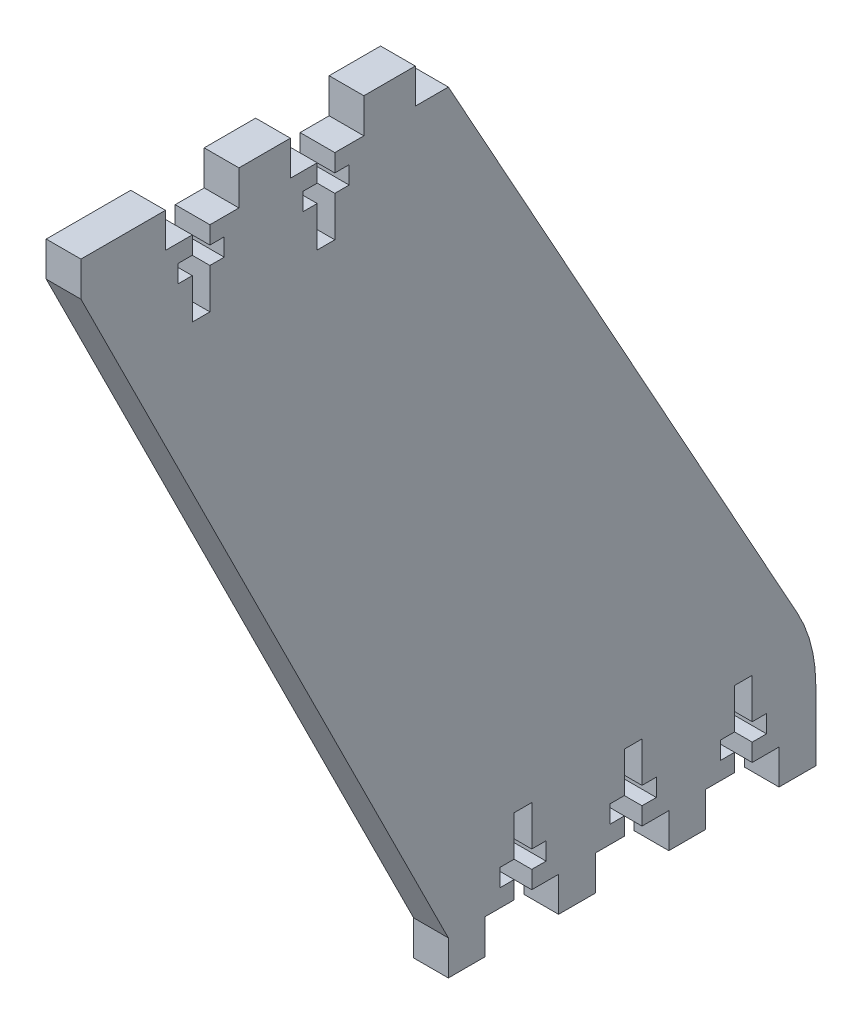
SolidWorks part; units mm, degrees
ref_plane "Front Plane" through (0, 0, 0) normal (0, 0, 1) x (1, 0, 0)
ref_plane "Top Plane" through (0, 0, 0) normal (0, 1, 0) x (1, 0, 0)
ref_plane "Right Plane" through (0, 0, 0) normal (1, 0, 0) x (0, 0, -1)
sketch "Sketch1" plane through (0, 0, 0) normal (1, 0, 0) x (0, 0, -1)
  line L0 (-74.3254, 0) -> (74.3254, 0) construction
  line L1 (-31.75, 0) -> (-95.25, 127.35)
  line L4 (-31.75, 0) -> (0, 17.1799) construction
  line L5 (-95.25, 127.35) -> (-95.25, 133.35)
  line L6 (-95.25, 133.35) -> (-80.645, 133.35)
  line L7 (-80.645, 133.35) -> (-80.645, 127.35)
  line L8 (-80.645, 127.35) -> (-67.945, 127.35)
  line L9 (-67.945, 127.35) -> (-67.945, 133.35)
  line L10 (-67.945, 133.35) -> (-59.055, 133.35)
  line L11 (-59.055, 133.35) -> (-59.055, 127.35)
  line L12 (-59.055, 127.35) -> (-46.355, 127.35)
  line L13 (-46.355, 127.35) -> (-46.355, 133.35)
  line L14 (-46.355, 133.35) -> (-37.465, 133.35)
  line L15 (-37.465, 133.35) -> (-37.465, 127.35)
  line L16 (-37.465, 127.35) -> (-31.75, 127.35)
  line L17 (-31.75, 0) -> (-31.75, -6)
  line L18 (-31.75, -6) -> (-25.4, -6)
  line L19 (-25.4, -6) -> (-25.4, 0)
  line L20 (-25.4, 0) -> (-12.7, 0)
  line L21 (-12.7, 0) -> (-12.7, -6)
  line L22 (-12.7, -6) -> (-6.35, -6)
  line L23 (-6.35, -6) -> (-6.35, 0)
  line L24 (-6.35, 0) -> (6.35, 0)
  line L25 (6.35, 0) -> (6.35, -6)
  line L26 (6.35, -6) -> (12.7, -6)
  line L27 (12.7, -6) -> (12.7, 0)
  line L28 (12.7, 0) -> (25.4, 0)
  line L29 (25.4, 0) -> (25.4, -6)
  line L30 (25.4, -6) -> (31.75, -6)
  line L31 (31.75, -6) -> (31.75, 0)
  line L32 (0, 17.1799) -> (31.75, 0) construction
  line L33 (0, 0) -> (0, 17.1799) construction
  line L34 (-63.5, 133.35) -> (-63.5, 108.2099) construction
  line L35 (31.75, 0) -> (31.75, 6.1358)
  line L36 (28.5696, 18.4423) -> (-31.75, 127.35)
  arc A0 (31.75, 6.1358) -> (28.5696, 18.4423) centre (6.35, 6.1358) ccw
  point P37 (-74.295, 127.35)
  point P38 (-52.705, 127.35)
  point P39 (-19.05, 0)
  point P40 (19.05, 0)
  point P44 (31.75, 12.7)
  line B0 (-18.8595, 13.05) -> (-18.8595, -5.9362) construction
  line B1 (-20.3835, 0) -> (-20.3835, 3.048)
  line B2 (-20.3835, 3.048) -> (-22.86, 3.048)
  line B3 (-22.86, 3.048) -> (-22.86, 6.096)
  line B4 (-22.86, 6.096) -> (-20.3835, 6.096)
  line B5 (-20.3835, 6.096) -> (-20.3835, 13.05)
  line B6 (-20.3835, 13.05) -> (-17.3355, 13.05)
  line B7 (-17.3355, 6.096) -> (-17.3355, 13.05)
  line B8 (-14.859, 6.096) -> (-17.3355, 6.096)
  line B9 (-14.859, 3.048) -> (-14.859, 6.096)
  line B10 (-17.3355, 3.048) -> (-14.859, 3.048)
  line B11 (-17.3355, 0) -> (-17.3355, 3.048)
  line B12 (0.1905, 13.05) -> (0.1905, -5.9362) construction
  line B13 (-1.3335, 0) -> (-1.3335, 3.048)
  line B14 (-1.3335, 3.048) -> (-3.81, 3.048)
  line B15 (-3.81, 3.048) -> (-3.81, 6.096)
  line B16 (-3.81, 6.096) -> (-1.3335, 6.096)
  line B17 (-1.3335, 6.096) -> (-1.3335, 13.05)
  line B18 (-1.3335, 13.05) -> (1.7145, 13.05)
  line B19 (1.7145, 6.096) -> (1.7145, 13.05)
  line B20 (4.191, 6.096) -> (1.7145, 6.096)
  line B21 (4.191, 3.048) -> (4.191, 6.096)
  line B22 (1.7145, 3.048) -> (4.191, 3.048)
  line B23 (1.7145, 0) -> (1.7145, 3.048)
  line B24 (19.2405, 13.05) -> (19.2405, -5.9362) construction
  line B25 (17.7165, 0) -> (17.7165, 3.048)
  line B26 (17.7165, 3.048) -> (15.24, 3.048)
  line B27 (15.24, 3.048) -> (15.24, 6.096)
  line B28 (15.24, 6.096) -> (17.7165, 6.096)
  line B29 (17.7165, 6.096) -> (17.7165, 13.05)
  line B30 (17.7165, 13.05) -> (20.7645, 13.05)
  line B31 (20.7645, 6.096) -> (20.7645, 13.05)
  line B32 (23.241, 6.096) -> (20.7645, 6.096)
  line B33 (23.241, 3.048) -> (23.241, 6.096)
  line B34 (20.7645, 3.048) -> (23.241, 3.048)
  line B35 (20.7645, 0) -> (20.7645, 3.048)
  line B36 (-74.4855, 114.3) -> (-74.4855, 133.2862) construction
  line B37 (-72.9615, 127.35) -> (-72.9615, 124.302)
  line B38 (-72.9615, 124.302) -> (-70.485, 124.302)
  line B39 (-70.485, 124.302) -> (-70.485, 121.254)
  line B40 (-70.485, 121.254) -> (-72.9615, 121.254)
  line B41 (-72.9615, 121.254) -> (-72.9615, 114.3)
  line B42 (-72.9615, 114.3) -> (-76.0095, 114.3)
  line B43 (-76.0095, 121.254) -> (-76.0095, 114.3)
  line B44 (-78.486, 121.254) -> (-76.0095, 121.254)
  line B45 (-78.486, 124.302) -> (-78.486, 121.254)
  line B46 (-76.0095, 124.302) -> (-78.486, 124.302)
  line B47 (-76.0095, 127.35) -> (-76.0095, 124.302)
  line B48 (-52.8955, 114.3) -> (-52.8955, 133.2862) construction
  line B49 (-51.3715, 127.35) -> (-51.3715, 124.302)
  line B50 (-51.3715, 124.302) -> (-48.895, 124.302)
  line B51 (-48.895, 124.302) -> (-48.895, 121.254)
  line B52 (-48.895, 121.254) -> (-51.3715, 121.254)
  line B53 (-51.3715, 121.254) -> (-51.3715, 114.3)
  line B54 (-51.3715, 114.3) -> (-54.4195, 114.3)
  line B55 (-54.4195, 121.254) -> (-54.4195, 114.3)
  line B56 (-56.896, 121.254) -> (-54.4195, 121.254)
  line B57 (-56.896, 124.302) -> (-56.896, 121.254)
  line B58 (-54.4195, 124.302) -> (-56.896, 124.302)
  line B59 (-54.4195, 127.35) -> (-54.4195, 124.302)
sketch_block_instance "Block-6-32x0_625 T-Nut block-1"
sketch_block "Block-6-32x0_625 T-Nut block" parameters "D1"=3.048, "D2"=13.05, "D3"=8.001, "D4"=3.048, "D5"=3.048
sketch_block_instance "Block-6-32x0_625 T-Nut block-2"
sketch_block_instance "Block-6-32x0_625 T-Nut block-3"
sketch_block_instance "Block-6-32x0_625 T-Nut block-5"
sketch_block_instance "Block-6-32x0_625 T-Nut block-6" parameters "D12"=25.4, "D1"=141.4375, "D2"=89.2054, "D3"=17.7034, "D4"=8.9474, "D5"=10.3714, "D6"=8.89, "D7"=11.0685, "D8"=24.0265, "D9"=6.0015, "D10"=6.35, "D11"=148.6509, "D13"=8.89, "D14"=5.715, "D15"=1.905
extrude "Boss-Extrude1" add sketch "Sketch1" along normal blind 6
